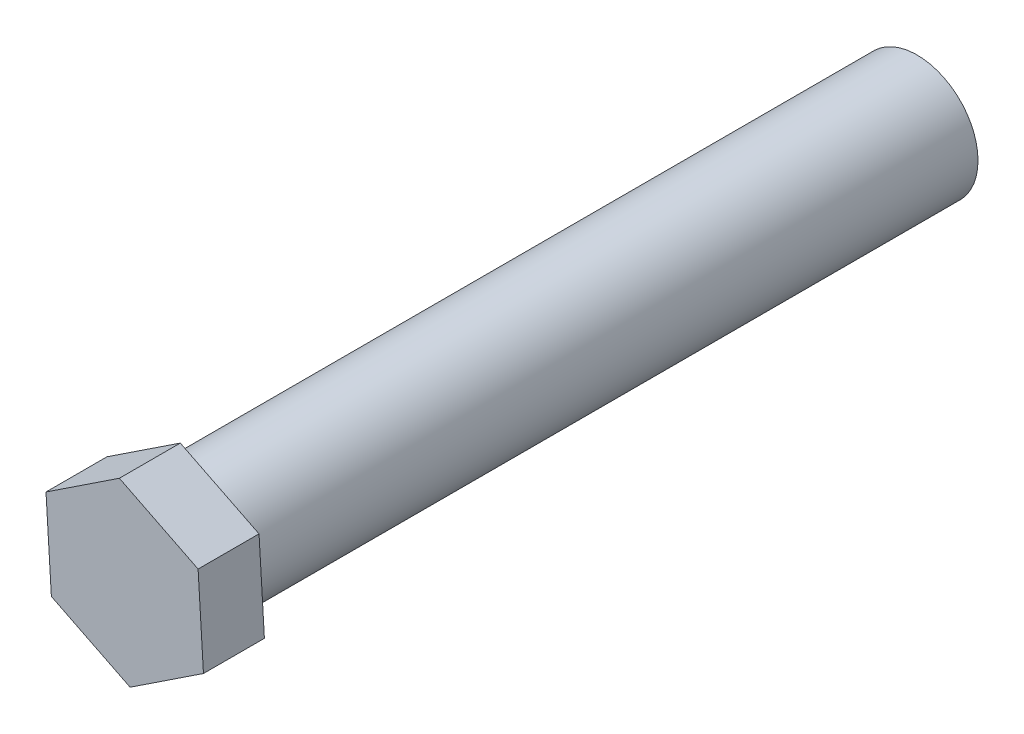
SolidWorks part; units mm, degrees
material "AISI 1020"
ref_plane "Alzado" through (0, 0, 0) normal (0, 0, 1) x (1, 0, 0)
ref_plane "Planta" through (0, 0, 0) normal (0, 1, 0) x (1, 0, 0)
ref_plane "Vista lateral" through (0, 0, 0) normal (1, 0, 0) x (0, 0, -1)
sketch "Croquis1" plane through (0, 0, 0) normal (0, 0, 1) x (1, 0, 0)
  circle A0 centre (0, 0) radius 6.35
  dimension "D1" = 12.7
extrude "Saliente-Extruir1" add sketch "Croquis1" against normal blind 76.2
sketch "Croquis2" plane through (0, 0, 0) normal (0, 0, 1) x (1, 0, 0)
  line L1 (8.2024, -4.0897) -> (7.643, 5.0587)
  line L2 (7.643, 5.0587) -> (-0.5594, 9.1483)
  line L3 (-0.5594, 9.1483) -> (-8.2024, 4.0897)
  line L4 (-8.2024, 4.0897) -> (-7.643, -5.0587)
  line L5 (-7.643, -5.0587) -> (0.5594, -9.1483)
  line L6 (0.5594, -9.1483) -> (8.2024, -4.0897)
  circle A0 centre (0, 0) radius 7.9375 construction
  dimension "D1" = 15.875
extrude "Saliente-Extruir2" add sketch "Croquis2" along normal blind 6.35
